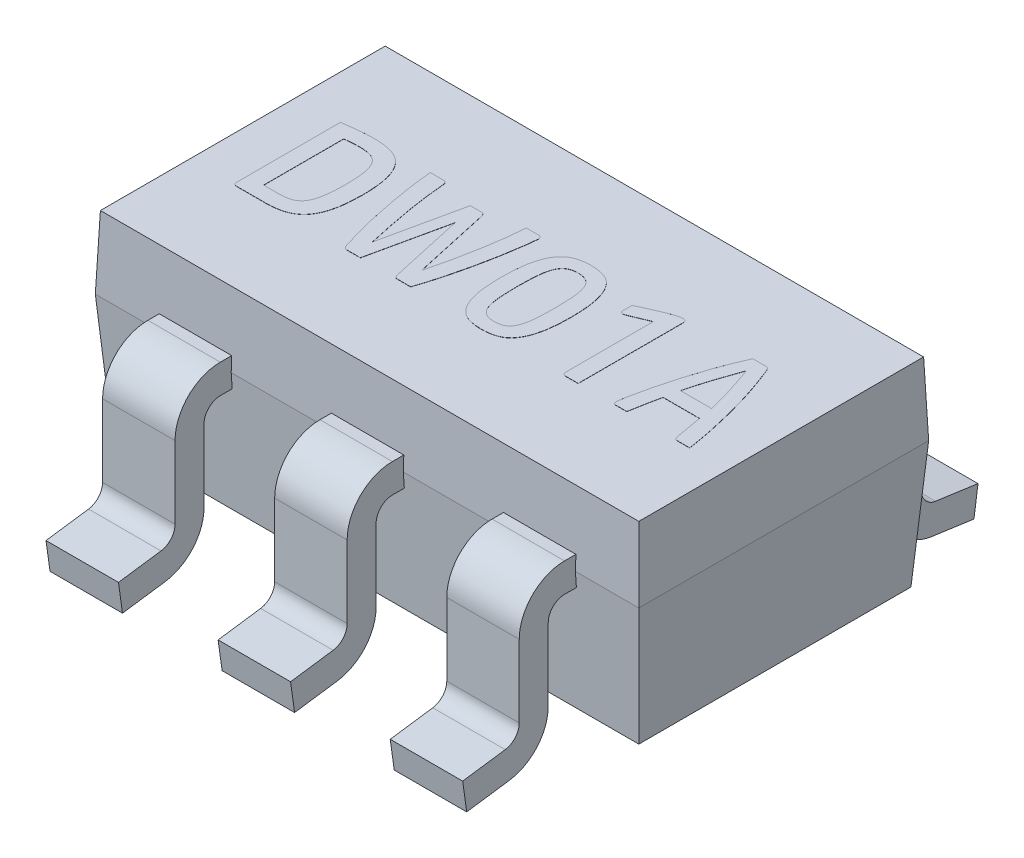
SolidWorks part; units mm, degrees
ref_plane "Front" through (0, 0, 0) normal (0, 0, 1) x (1, 0, 0)
ref_plane "Top" through (0, 0, 0) normal (0, 1, 0) x (1, 0, 0)
ref_plane "Right" through (0, 0, 0) normal (1, 0, 0) x (0, 0, -1)
sketch "Sketch1" plane through (0, 0, 0) normal (0, 1, 0) x (1, 0, 0)
  line L1 (-1.5, -0.8) -> (1.5, -0.8)
  line L2 (-1.5, -0.8) -> (-1.5, 0.8)
  line L3 (-1.5, 0.8) -> (1.5, 0.8)
  line L4 (1.5, -0.8) -> (1.5, 0.8)
  line L5 (-1.5, -0.8) -> (1.5, 0.8) construction
  line L6 (-1.5, 0.8) -> (1.5, -0.8) construction
  point P0 (0, 0)
  dimension "D1" = 3
  dimension "D2" = 1.6
extrude "Extrude1" add sketch "Sketch1" along normal blind 0.4 draft 2 and the other way blind 0.7 draft 4
ref_plane "Plane1" through (0.95, 0, 0) normal (1, 0, 0) x (0, 0, -1)
sketch "Sketch5" plane through (0.95, 0, 0) normal (1, 0, 0) x (0, 0, -1)
  line L0 (0, 0.08) -> (-0.86, 0.08)
  line L1 (-1.11, -0.17) -> (-1.11, -0.5694)
  line L2 (-1.1875, -0.6586) -> (-1.4223, -0.6916)
  line L3 (0, -0.08) -> (-0.86, -0.08)
  line L4 (0, 0.08) -> (0, -0.08) construction
  line L5 (-1.4223, -0.6916) -> (-1.4, -0.85)
  line L6 (-0.95, -0.17) -> (-0.95, -0.5694)
  line L7 (-1.1652, -0.817) -> (-1.4, -0.85)
  line L9 (10.6727, 0) -> (-10.6727, 0) construction
  line L10 (-0.7511, -0.7) -> (0.7511, -0.7) construction
  line L12 (0, 3.8593) -> (0, -3.8593) construction
  line L13 (1.1652, -0.817) -> (1.4, -0.85)
  line L14 (0.95, -0.17) -> (0.95, -0.5694)
  line L15 (1.4223, -0.6916) -> (1.4, -0.85)
  line L16 (0, -0.08) -> (0.86, -0.08)
  line L17 (1.1875, -0.6586) -> (1.4223, -0.6916)
  line L18 (1.11, -0.17) -> (1.11, -0.5694)
  line L19 (0, 0.08) -> (0.86, 0.08)
  arc A0 (-1.11, -0.5694) -> (-1.1875, -0.6586) centre (-1.2, -0.5694) cw
  arc A1 (-0.86, 0.08) -> (-1.11, -0.17) centre (-0.86, -0.17) ccw
  arc A2 (-0.86, -0.08) -> (-0.95, -0.17) centre (-0.86, -0.17) ccw
  arc A3 (-0.95, -0.5694) -> (-1.1652, -0.817) centre (-1.2, -0.5694) cw
  arc A4 (0.95, -0.5694) -> (1.1652, -0.817) centre (1.2, -0.5694) ccw
  arc A5 (0.86, -0.08) -> (0.95, -0.17) centre (0.86, -0.17) cw
  arc A6 (0.86, 0.08) -> (1.11, -0.17) centre (0.86, -0.17) cw
  arc A7 (1.11, -0.5694) -> (1.1875, -0.6586) centre (1.2, -0.5694) ccw
  arc A8 (-0.86, 0.08) -> (-1.11, -0.17) centre (-0.86, -0.17) ccw construction
  arc A9 (-1.11, -0.5694) -> (-1.1875, -0.6586) centre (-1.2, -0.5694) cw construction
  point P13 (-1.11, -0.6477)
  dimension "D6" = 0.15
  dimension "D7" = 0.45
  dimension "D5" = 0.25
  dimension "D1" = 0.16
  dimension "D2" = 0.08
  dimension "D3" = 8
  dimension "D4" = 1.4
extrude "Extrude3" add sketch "Sketch5" along normal mid plane 0.4
pattern_linear "LPattern3" count 3 spacing 0.95 along (-1, 0, 0) of "Extrude3"
sketch "Sketch6" plane through (0, 0.4, 0) normal (0, 1, 0) x (1, 0, 0)
  line L0 (-1.486, -0.295) -> (1.486, -0.295) construction
  line L1 (-1.486, 0.786) -> (-1.486, -0.786) construction
  line L2 (1.486, -0.786) -> (1.486, 0.786) construction
  text T0 "DW01A" font "HP Simplified" height 0.6
extrude "Boss-Extrude1" add sketch "Sketch6" along normal blind 0.001
